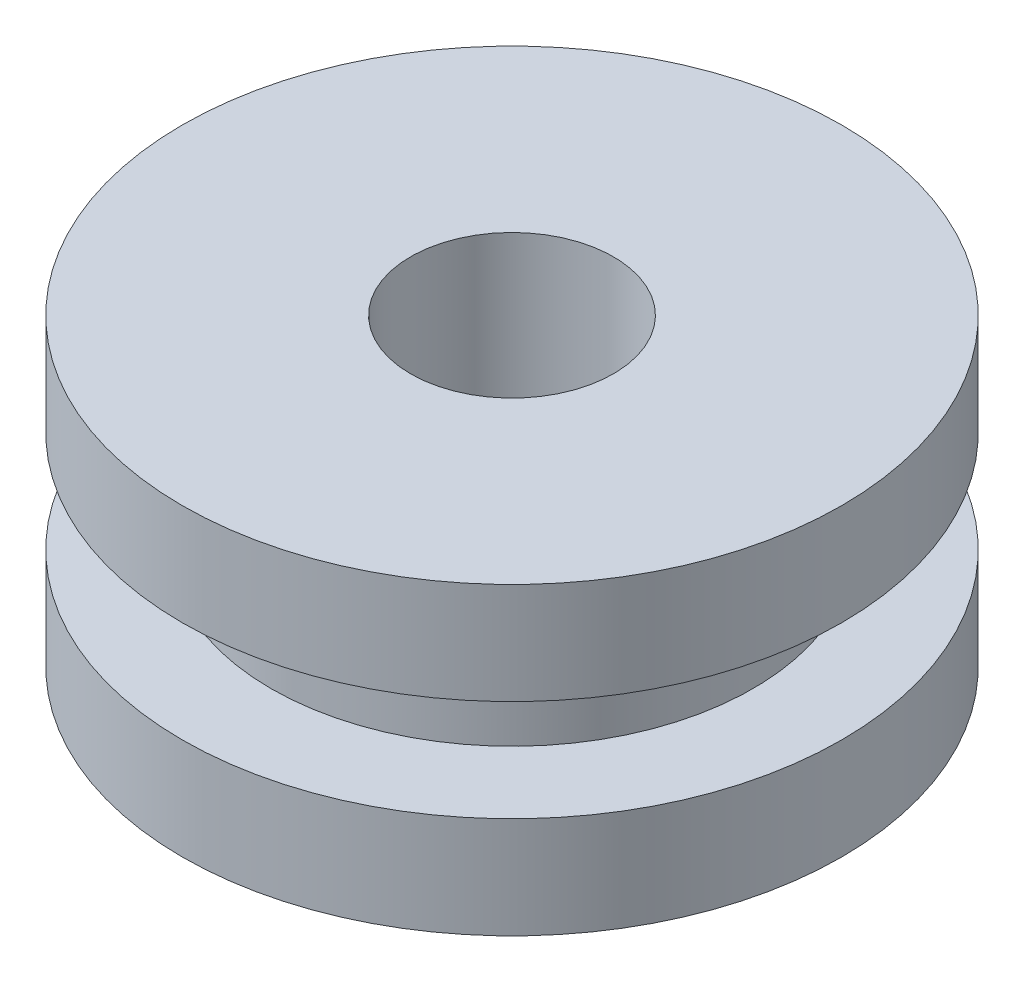
SolidWorks part; units mm, degrees
ref_plane "前视基准面" through (0, 0, 0) normal (0, 0, 1) x (1, 0, 0)
ref_plane "上视基准面" through (0, 0, 0) normal (0, 1, 0) x (1, 0, 0)
ref_plane "右视基准面" through (0, 0, 0) normal (1, 0, 0) x (0, 0, -1)
sketch "草图1" plane through (0, 0, 0) normal (0, 1, 0) x (1, 0, 0)
  circle A0 centre (0, 0) radius 2
  circle A1 centre (0, 0) radius 6.5
  dimension "D1" = 4
  dimension "D2" = 13
extrude "凸台-拉伸1" add sketch "草图1" along normal blind 6
ref_plane "基准面1" through (0, 3, 0) normal (0, 1, 0) x (1, 0, 0)
sketch "草图4" plane through (0, 3, 0) normal (0, 1, 0) x (1, 0, 0)
  circle A0 centre (0, 0) radius 4.75
  circle A1 centre (0, 0) radius 7
  dimension "D1" = 9.5
  dimension "D2" = 14
extrude "切除-拉伸1" cut sketch "草图4" against normal blind 1 and the other way blind 1
